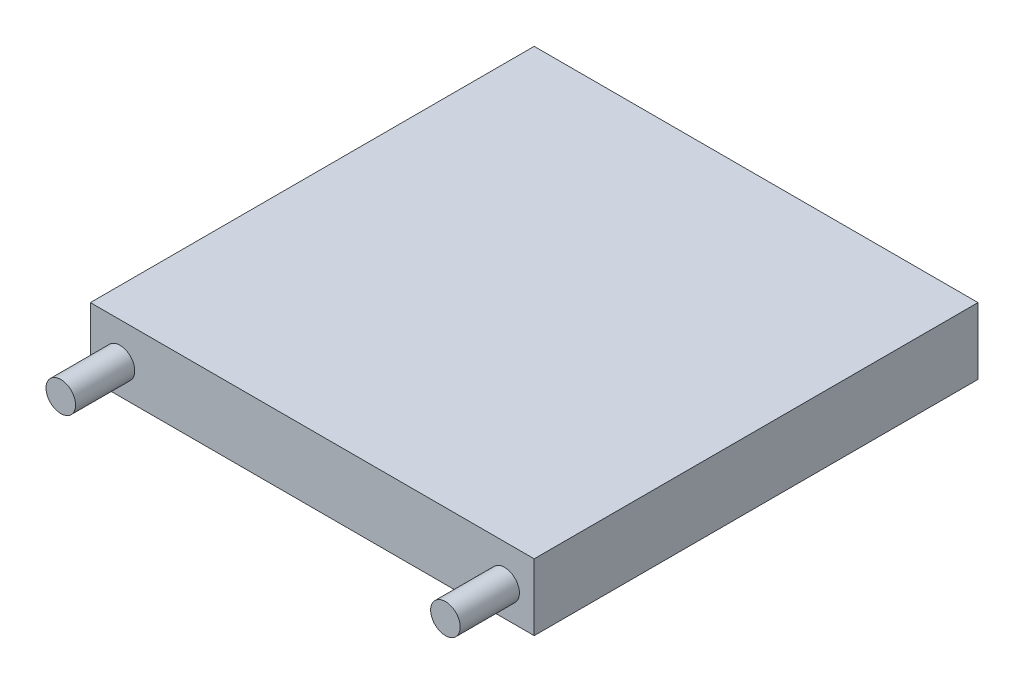
SolidWorks part; units mm, degrees
ref_plane "Front Plane" through (0, 0, 0) normal (0, 0, 1) x (1, 0, 0)
ref_plane "Top Plane" through (0, 0, 0) normal (0, 1, 0) x (1, 0, 0)
ref_plane "Right Plane" through (0, 0, 0) normal (1, 0, 0) x (0, 0, -1)
sketch "Sketch1" plane through (0, 0, 0) normal (0, 1, 0) x (1, 0, 0)
  line L1 (-15, -15) -> (15, -15)
  line L2 (-15, -15) -> (-15, 15)
  line L3 (-15, 15) -> (15, 15)
  line L4 (15, -15) -> (15, 15)
  line L5 (-15, -15) -> (15, 15) construction
  line L6 (-15, 15) -> (15, -15) construction
  point P0 (0, 0)
  dimension "D1" = 30
  dimension "D2" = 30
extrude "Boss-Extrude1" add sketch "Sketch1" along normal blind 4.5
sketch "Sketch2" plane through (0, 0, 15) normal (0, 0, 1) x (1, 0, 0)
  line L1 (-15, 4.5) -> (-15, 0) construction
  line L2 (0, 0) -> (0, 7.4727) construction
  circle A0 centre (-13, 2) radius 1
  circle A1 centre (13, 2) radius 1
  dimension "D1" = 2
  dimension "D2" = 2
extrude "Boss-Extrude2" add sketch "Sketch2" along normal blind 4
